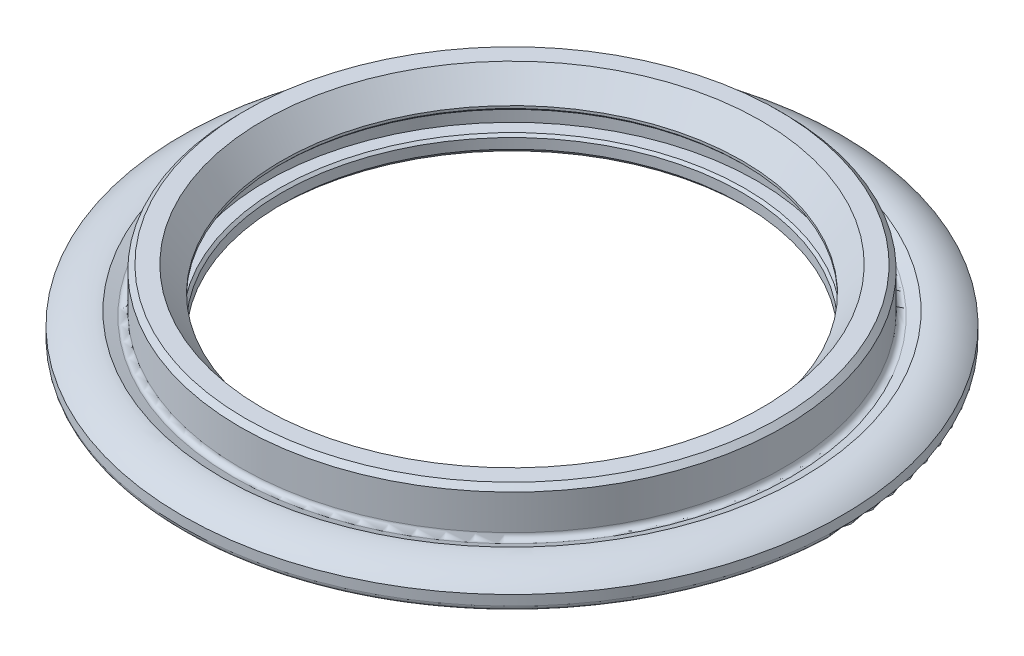
SolidWorks part; units mm, degrees
ref_plane "Plano frontal" through (0, 0, 0) normal (0, 0, 1) x (1, 0, 0)
ref_plane "Plano superior" through (0, 0, 0) normal (0, 1, 0) x (1, 0, 0)
ref_plane "Plano direito" through (0, 0, 0) normal (1, 0, 0) x (0, 0, -1)
sketch "Esboço1" plane through (0, 0, 0) normal (0, 0, 1) x (1, 0, 0)
  line L0 (0, -63.3291) -> (0, 63.8035) construction
  line L1 (58, 0) -> (61, 2)
  line L2 (57.5, 5.5) -> (54, 4)
  line L3 (54, 4) -> (54, 13.5)
  line L4 (54, 13.5) -> (49.5, 13.5)
  line L5 (49.5, 13.5) -> (45.75, 8.5)
  line L6 (45.75, 8.5) -> (45.75, 7.5)
  line L7 (45.75, 7.5) -> (48.75, 7.5)
  line L8 (48.75, 7.5) -> (48.75, 3.5)
  line L9 (48.75, 3.5) -> (45.75, 3.5)
  line L10 (45.75, 3.5) -> (45.75, 0)
  line L11 (45.75, 0) -> (58, 0)
  line L12 (61, 2) -> (63.6667, 0)
  line L13 (63.6667, 0) -> (65.5, 0)
  line L14 (65.5, 0) -> (65.5, 3)
  arc A0 (57.5, 5.5) -> (65.5, 3) centre (58.7918, -4.4162) cw
  dimension "D14" = 61
  dimension "D13" = 58
  dimension "D15" = 2
  dimension "D17" = 10
  dimension "D1" = 45.75
  dimension "D2" = 45.75
  dimension "D3" = 48.75
  dimension "D4" = 49.5
  dimension "D5" = 5
  dimension "D6" = 54
  dimension "D7" = 57.5
  dimension "D8" = 9.5
  dimension "D9" = 8
  dimension "D10" = 6
  dimension "D11" = 10
  dimension "D12" = 13.5
  dimension "D16" = 65.5
  dimension "D18" = 3
revolve "Revolução1" add sketch "Esboço1" angle 360 about L0
fillet "Filete1" radius 2 1 edges at (0, 2, -61)
fillet "Filete2" radius 1 1 edges at (0, 0, -63.6667)
fillet "Filete3" radius 1 1 edges at (0, 0, -65.5)
chamfer "Chanfro1" distance 1 angle 45 1 edges at (0, 0, -45.75)
chamfer "Chanfro2" distance 0.5 angle 45 2 edges at (0, 3.5, -45.75) (0, 7.5, -45.75)
chamfer "Chanfro3" distance 1 angle 45 1 edges at (0, 13.5, -54)
fillet "Filete4" radius 1 1 edges at (0, 4, -54)
